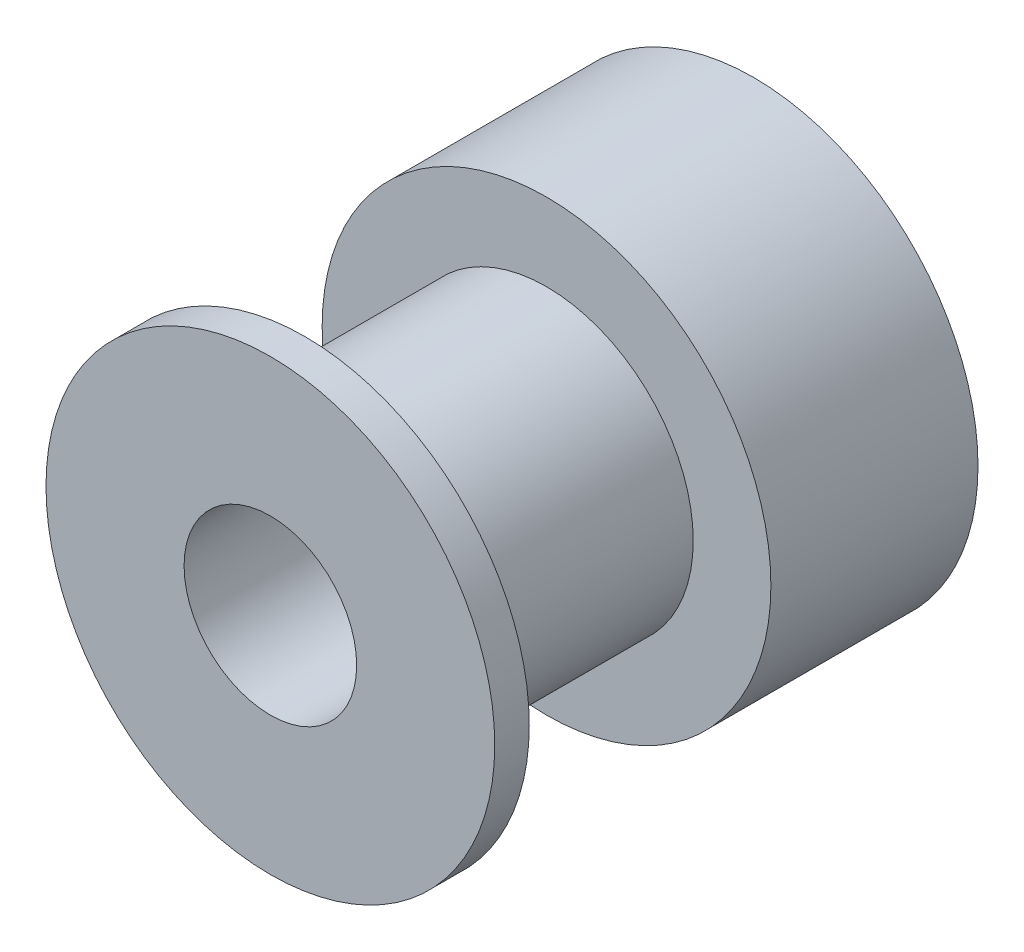
SolidWorks part; units mm, degrees
ref_plane "前视基准面" through (0, 0, 0) normal (0, 0, 1) x (1, 0, 0)
ref_plane "上视基准面" through (0, 0, 0) normal (0, 1, 0) x (1, 0, 0)
ref_plane "右视基准面" through (0, 0, 0) normal (1, 0, 0) x (0, 0, -1)
sketch "草图1" plane through (0, 0, 0) normal (0, 0, 1) x (1, 0, 0)
  circle A0 centre (0, 0) radius 6.5
extrude "凸台-拉伸1" add sketch "草图1" along normal blind 6
sketch "草图2" plane through (0, 0, 6) normal (0, 0, 1) x (1, 0, 0)
  circle A0 centre (0, 0) radius 4.25
extrude "凸台-拉伸2" add sketch "草图2" along normal blind 7
sketch "草图3" plane through (0, 0, 13) normal (0, 0, 1) x (1, 0, 0)
  circle A0 centre (0, 0) radius 6.5
extrude "凸台-拉伸3" add sketch "草图3" along normal blind 1
sketch "草图4" plane through (0, 0, 14) normal (0, 0, 1) x (1, 0, 0)
  circle A1 centre (0, 0) radius 2.5
extrude "切除-拉伸1" cut sketch "草图4" against normal blind 34
sketch "草图5" plane through (0, 0, 0) normal (0, 1, 0) x (1, 0, 0)
  circle A0 centre (0, -3) radius 1.5
extrude "切除-拉伸2" cut sketch "草图5" against normal blind 10
sketch "草图6" plane through (0, 0, 0) normal (1, 0, 0) x (0, 0, -1)
  circle A0 centre (-3, 0) radius 1.5
extrude "切除-拉伸3" cut sketch "草图6" against normal blind 10
